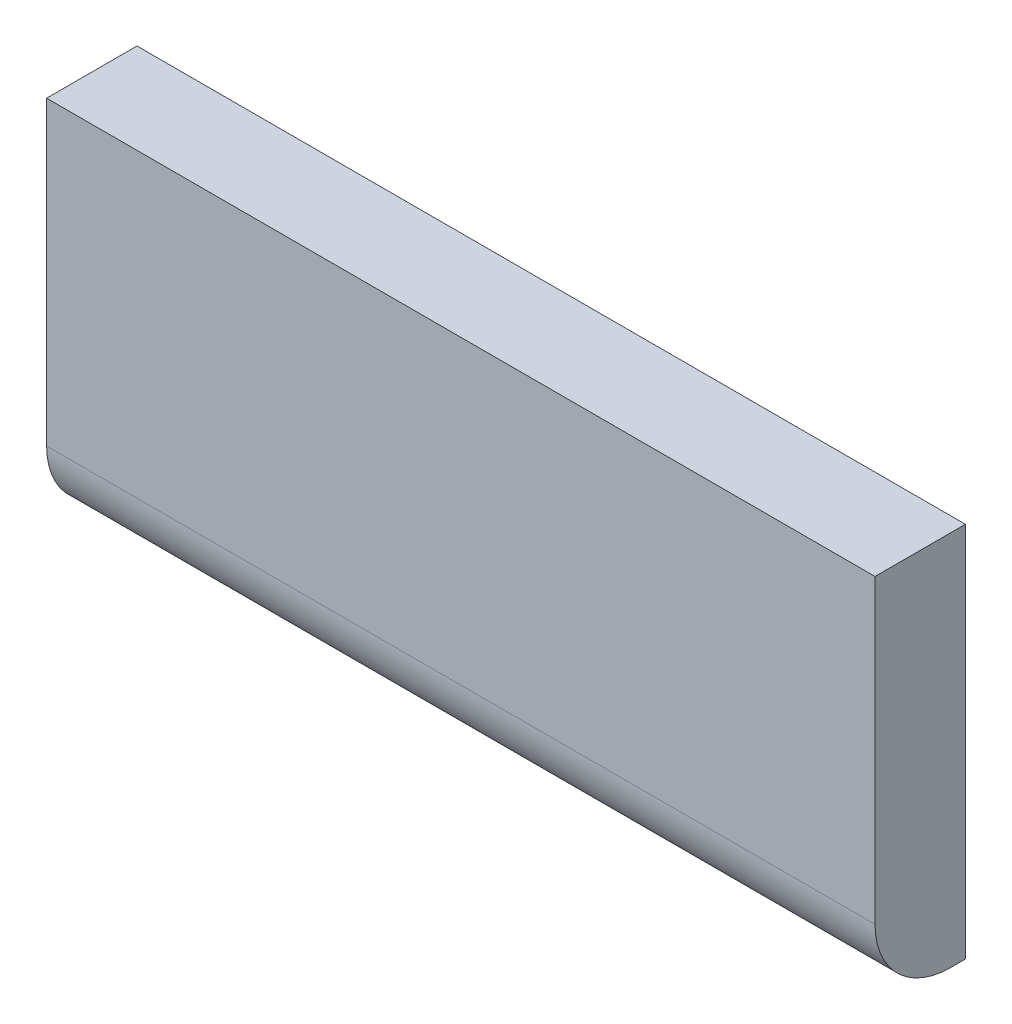
SolidWorks part; units mm, degrees
ref_plane "Front Plane" through (0, 0, 0) normal (0, 0, 1) x (1, 0, 0)
ref_plane "Top Plane" through (0, 0, 0) normal (0, 1, 0) x (1, 0, 0)
ref_plane "Right Plane" through (0, 0, 0) normal (1, 0, 0) x (0, 0, -1)
sketch "Sketch1" plane through (0, 0, 0) normal (0, 0, 1) x (1, 0, 0)
  line L1 (-27.5, 12.5) -> (27.5, 12.5)
  line L2 (-27.5, 12.5) -> (-27.5, -12.5)
  line L3 (-27.5, -12.5) -> (27.5, -12.5)
  line L4 (27.5, 12.5) -> (27.5, -12.5)
  line L5 (-27.5, 12.5) -> (27.5, -12.5) construction
  line L6 (-27.5, -12.5) -> (27.5, 12.5) construction
  point P0 (0, 0)
  dimension "D1" = 55
  dimension "D2" = 25
extrude "Boss-Extrude1" add sketch "Sketch1" along normal blind 6
fillet "Fillet1" radius 5 1 edges at (0, -12.5, 6)
